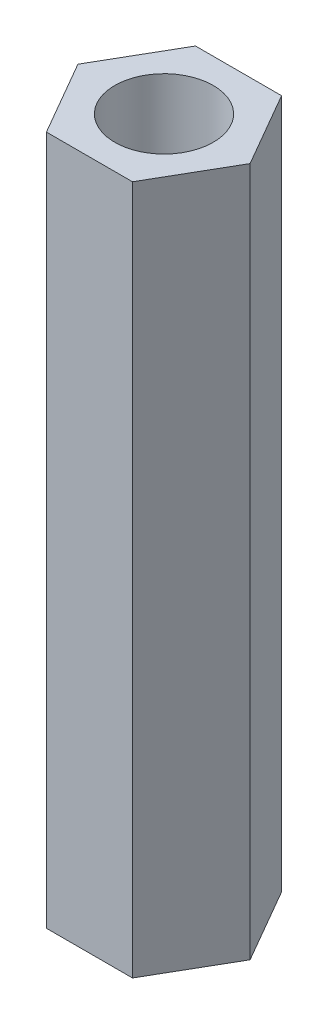
SolidWorks part; units mm, degrees
ref_plane "前视基准面" through (0, 0, 0) normal (0, 0, 1) x (1, 0, 0)
ref_plane "上视基准面" through (0, 0, 0) normal (0, 1, 0) x (1, 0, 0)
ref_plane "右视基准面" through (0, 0, 0) normal (1, 0, 0) x (0, 0, -1)
other "Configuration Table"
sketch "草图1" plane through (0, 0, 0) normal (0, 1, 0) x (1, 0, 0)
  line L1 (2.6212, 0) -> (1.3106, 2.27)
  line L2 (1.3106, 2.27) -> (-1.3106, 2.27)
  line L3 (-1.3106, 2.27) -> (-2.6212, 0)
  line L4 (-2.6212, 0) -> (-1.3106, -2.27)
  line L5 (-1.3106, -2.27) -> (1.3106, -2.27)
  line L6 (1.3106, -2.27) -> (2.6212, 0)
  circle A0 centre (0, 0) radius 2.27 construction
  circle A1 centre (0, 0) radius 1.5
  dimension "D1" = 4.54
  dimension "D2" = 3
extrude "凸台-拉伸1" add sketch "草图1" along normal blind 21
